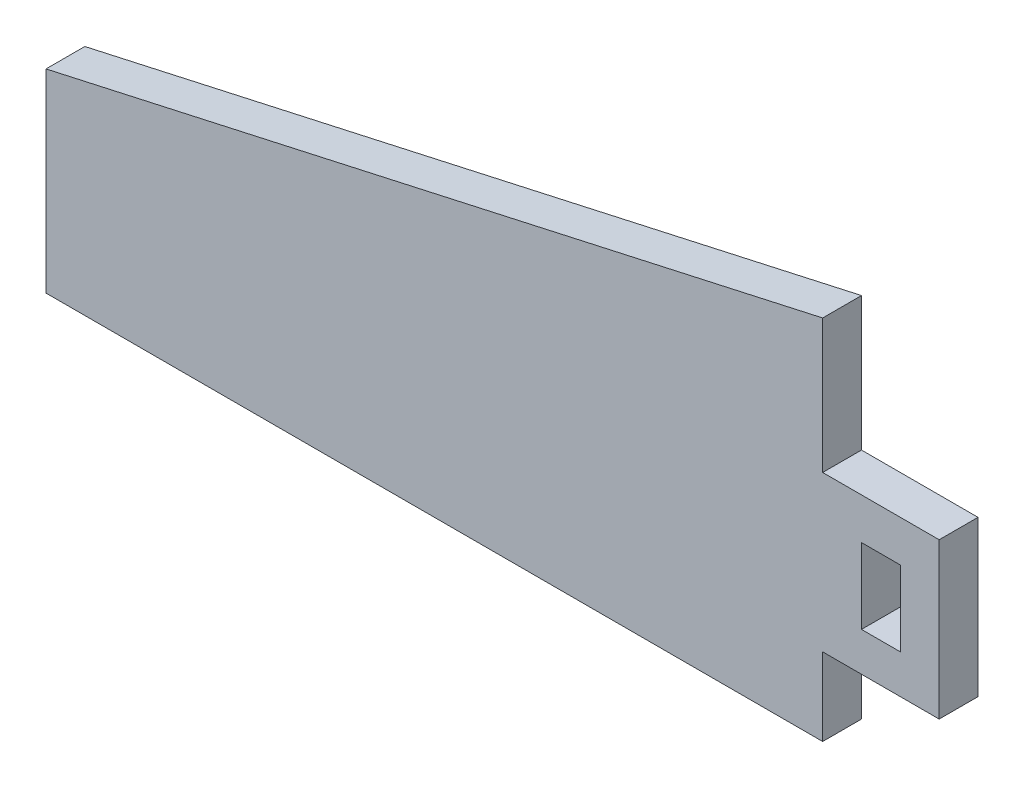
SolidWorks part; units mm, degrees
ref_plane "Спереди" through (0, 0, 0) normal (0, 0, 1) x (1, 0, 0)
ref_plane "Сверху" through (0, 0, 0) normal (0, 1, 0) x (1, 0, 0)
ref_plane "Справа" through (0, 0, 0) normal (1, 0, 0) x (0, 0, -1)
sketch "Sketch1" plane through (0, 0, 0) normal (0, 0, 1) x (1, 0, 0)
  line L0 (100, 30) -> (100, 47.2297)
  line L1 (0, 0) -> (100, 0)
  line L2 (0, 0) -> (0, 25)
  line L4 (100, 0) -> (100, 10)
  line L5 (100, 47.2297) -> (0, 25)
  line L7 (100, 30) -> (115, 30)
  line L9 (100, 10) -> (115, 10)
  line L10 (115, 30) -> (115, 10)
  line L11 (105, 24.6855) -> (110, 24.6855)
  line L12 (105, 24.6855) -> (105, 15)
  line L13 (105, 15) -> (110, 15)
  line L14 (110, 24.6855) -> (110, 15)
  dimension "D1" = 100
  dimension "D2" = 25
  dimension "D4" = 10
  dimension "D5" = 20
  dimension "D6" = 15
  dimension "D7" = 5
  dimension "D8" = 5
  dimension "D9" = 5
extrude "Boss-Extrude1" add sketch "Sketch1" along normal blind 5
